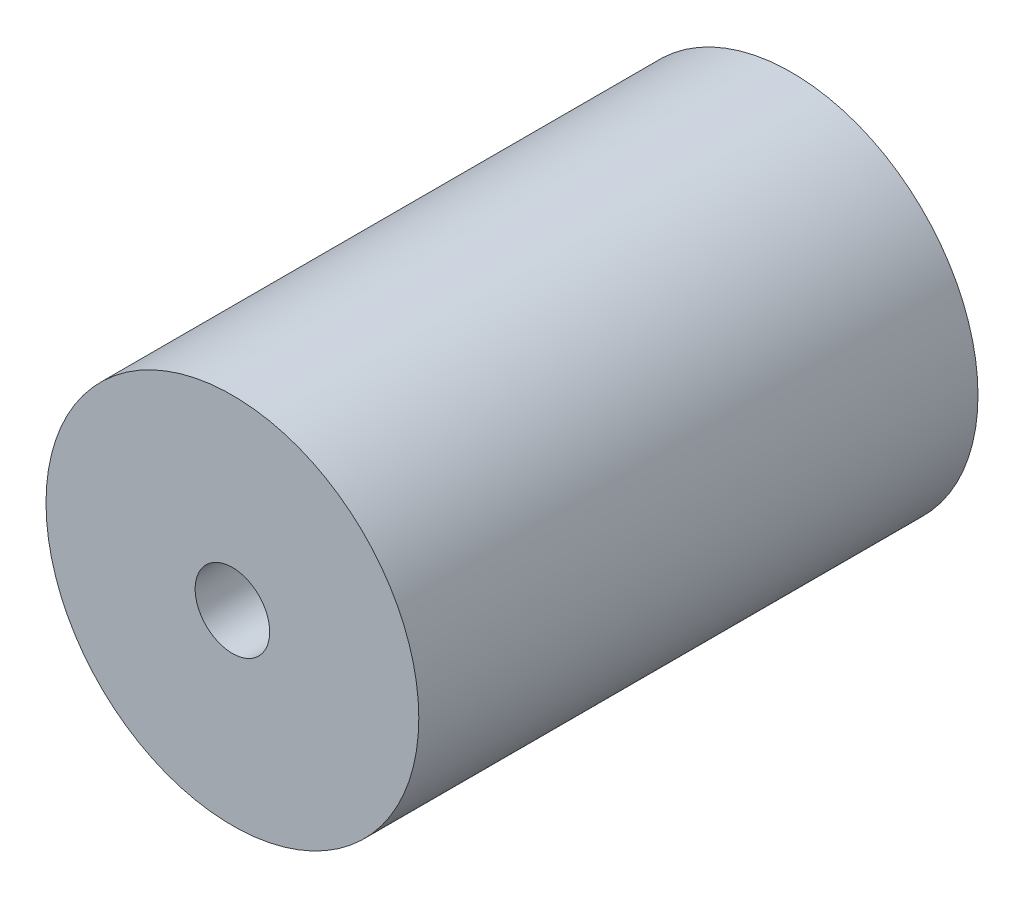
SolidWorks part; units mm, degrees
ref_plane "Front Plane" through (0, 0, 0) normal (0, 0, 1) x (1, 0, 0)
ref_plane "Top Plane" through (0, 0, 0) normal (0, 1, 0) x (1, 0, 0)
ref_plane "Right Plane" through (0, 0, 0) normal (1, 0, 0) x (0, 0, -1)
sketch "Sketch1" plane through (0, 0, 0) normal (0, 0, 1) x (1, 0, 0)
  circle A0 centre (0, 0) radius 10
  dimension "D1" = 20
extrude "Boss-Extrude1" add sketch "Sketch1" along normal blind 30
sketch "Sketch2" plane through (0, 0, 30) normal (0, 0, 1) x (1, 0, 0)
  circle A0 centre (0, 0) radius 2
  dimension "D1" = 4
extrude "Cut-Extrude1" cut sketch "Sketch2" against normal blind 30 contours A0
sketch "Sketch3" plane through (0, 0, 0) normal (0, 0, -1) x (-1, 0, 0)
  circle A0 centre (0, 0) radius 3
  dimension "D1" = 6
extrude "Cut-Extrude2" cut sketch "Sketch3" against normal blind 14
